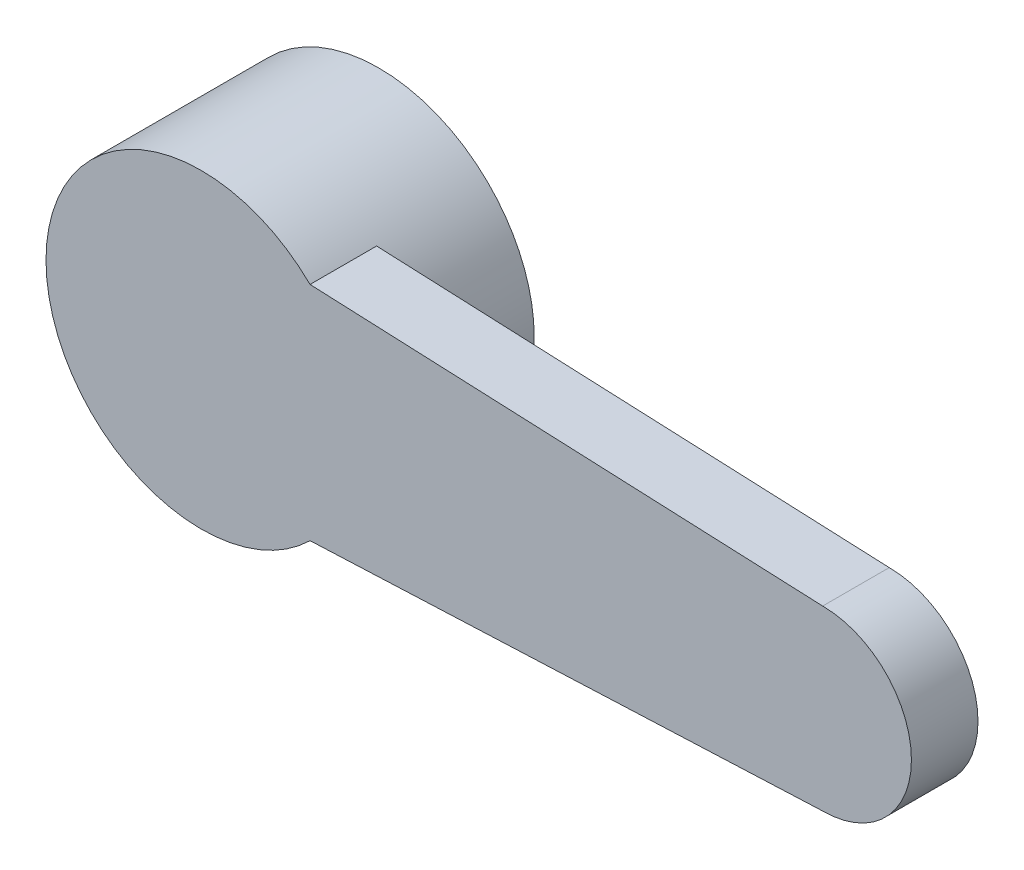
SolidWorks part; units mm, degrees
ref_plane "前视基准面" through (0, 0, 0) normal (0, 0, 1) x (1, 0, 0)
ref_plane "上视基准面" through (0, 0, 0) normal (0, 1, 0) x (1, 0, 0)
ref_plane "右视基准面" through (0, 0, 0) normal (1, 0, 0) x (0, 0, -1)
other "Configuration Table"
sketch "草图1" plane through (0, 0, 0) normal (0, 0, 1) x (1, 0, 0)
  circle A0 centre (0, 0) radius 3.5
  dimension "D1" = 7
extrude "凸台-拉伸1" add sketch "草图1" along normal blind 4
sketch "草图2" plane through (0, 0, 4) normal (0, 0, 1) x (1, 0, 0)
  line L0 (0, 0) -> (16, 0) construction
  line L1 (2.4495, 2.5) -> (14, 2)
  line L2 (14, -2) -> (14, 2) construction
  line L3 (2.4495, -2.5) -> (14, -2)
  line L4 (2.4495, -2.5) -> (2.4495, 2.5)
  circle A0 centre (0, 0) radius 3.5 construction
  arc A1 (14, 2) -> (14, -2) centre (14, 0) cw
  dimension "D3" = 14
  dimension "D4" = 2
  dimension "D1" = 4
  dimension "D2" = 5
extrude "凸台-拉伸2" add sketch "草图2" against normal blind 1.5
